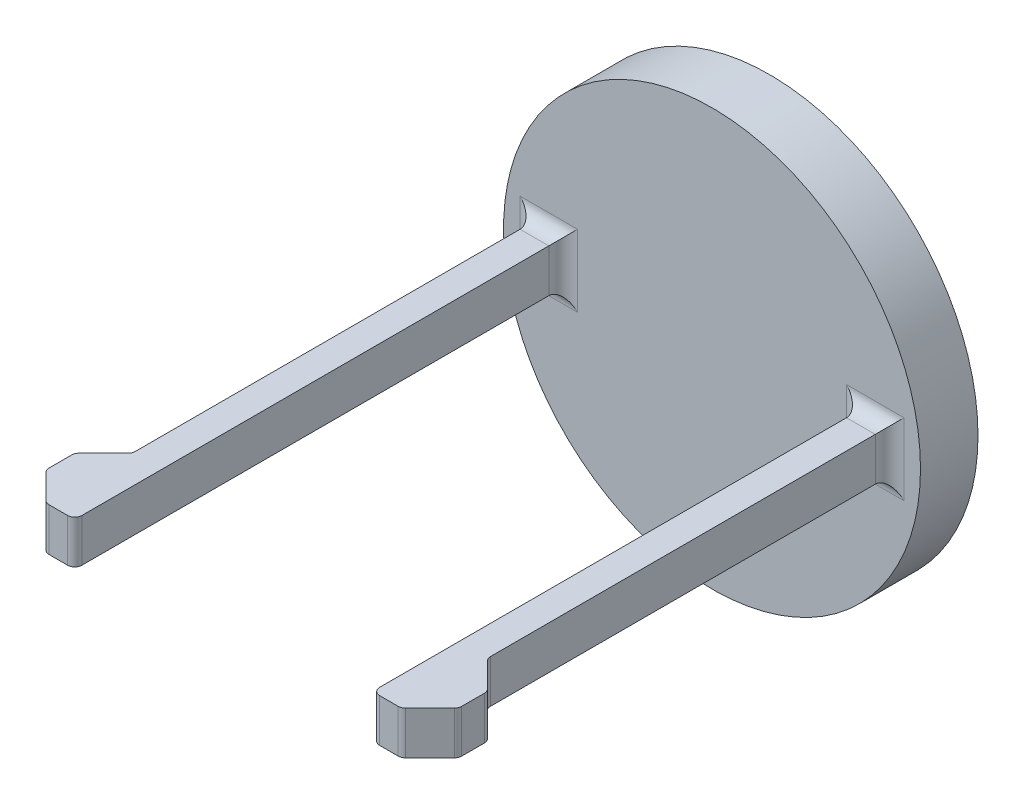
SolidWorks part; units mm, degrees
ref_plane "Front Plane" through (0, 0, 0) normal (1, 0, 0) x (0, 1, 0)
ref_plane "Top Plane" through (0, 0, 0) normal (0, 0, 1) x (0, 1, 0)
ref_plane "Right Plane" through (0, 0, 0) normal (0, 1, 0) x (-1, 0, 0)
sketch "Sketch1" plane through (0, 0, 0) normal (0, 0, 1) x (0, 1, 0)
  circle A0 centre (0, 0) radius 14.5
  dimension "D1" = 29
extrude "Boss-Extrude1" add sketch "Sketch1" along normal blind 4
sketch "Sketch2" plane through (0, 0, 4) normal (0, 0, 1) x (1, 0, 0)
  line L0 (0, 0) -> (-14.5, 0) construction
  line L1 (0, 0) -> (14.5, 0) construction
  line L2 (0, 14.5) -> (0, 0) construction
  line L3 (-12.3535, 1.5) -> (-10.3535, 1.5)
  line L4 (-12.3535, 1.5) -> (-12.3535, -1.5)
  line L5 (-12.3535, -1.5) -> (-10.3535, -1.5)
  line L6 (-10.3535, 1.5) -> (-10.3535, -1.5)
  line L7 (-12.3535, 1.5) -> (-10.3535, -1.5) construction
  line L8 (-12.3535, -1.5) -> (-10.3535, 1.5) construction
  line L9 (0, 0) -> (0, -14.5) construction
  line L10 (12.3535, -1.5) -> (10.3535, -1.5)
  line L11 (10.3535, 1.5) -> (10.3535, -1.5)
  line L12 (12.3535, 1.5) -> (10.3535, 1.5)
  line L13 (12.3535, 1.5) -> (12.3535, -1.5)
  circle A0 centre (0, 0) radius 14.5 construction
  point P6 (-11.3535, 0)
  dimension "D1" = 2
  dimension "D2" = 3
extrude "Boss-Extrude2" add sketch "Sketch2" along normal blind 33.9738
sketch "Sketch3" plane through (-12.3535, 0, 0) normal (-1, 0, 0) x (0, -1, 0)
  line L0 (-1.5, 37.9738) -> (1.5, 37.9738) construction
  line L1 (-1.5, 37.9738) -> (1.5, 37.9738)
  line L2 (-1.5, 37.9738) -> (-1.5, 31.9738)
  line L3 (-1.5, 31.9738) -> (1.5, 31.9738)
  line L4 (1.5, 37.9738) -> (1.5, 31.9738)
  line L5 (1.5, 37.9738) -> (1.5, 4) construction
  dimension "D1" = 6
extrude "Boss-Extrude3" add sketch "Sketch3" along normal blind 2
sketch "Sketch4" plane through (0, -1.5, 0) normal (0, -1, 0) x (1, 0, 0)
  line L0 (-12.3535, 31.9738) -> (-14.3535, 33.9738)
  line L1 (-14.3535, 31.9738) -> (-14.3535, 37.9738) construction
  line L2 (-12.3535, 37.9738) -> (-14.3535, 35.9738)
  line L3 (-14.3535, 37.9738) -> (-10.3535, 37.9738) construction
  line L4 (-14.3535, 31.9738) -> (-12.3535, 31.9738) construction
  line L5 (-14.3535, 33.9738) -> (-14.3535, 31.9738)
  line L6 (-14.3535, 31.9738) -> (-12.3535, 31.9738)
  line L7 (-14.3535, 35.9738) -> (-14.3535, 37.9738)
  line L8 (-14.3535, 37.9738) -> (-12.3535, 37.9738)
  dimension "D1" = 45
  dimension "D2" = 45
extrude "Cut-Extrude1" cut sketch "Sketch4" against normal up to next
sketch "Sketch5" plane through (12.3535, 0, 0) normal (1, 0, 0) x (0, 1, 0)
  line L0 (1.5, 37.9738) -> (1.5, 4) construction
  line L1 (-1.5, 37.9738) -> (1.5, 37.9738)
  line L2 (-1.5, 37.9738) -> (-1.5, 31.9738)
  line L3 (-1.5, 31.9738) -> (1.5, 31.9738)
  line L4 (1.5, 37.9738) -> (1.5, 31.9738)
  dimension "D1" = 6
extrude "Boss-Extrude4" add sketch "Sketch5" along normal blind 2
sketch "Sketch6" plane through (0, -1.5, 0) normal (0, -1, 0) x (1, 0, 0)
  line L0 (12.3535, 31.9738) -> (14.3535, 33.9738)
  line L1 (14.3535, 37.9738) -> (14.3535, 31.9738) construction
  line L2 (14.3535, 33.9738) -> (14.3535, 31.9738)
  line L3 (14.3535, 31.9738) -> (12.3535, 31.9738)
  line L4 (12.3535, 37.9738) -> (14.3535, 35.9738)
  line L5 (10.3535, 37.9738) -> (14.3535, 37.9738) construction
  line L6 (14.3535, 35.9738) -> (14.3535, 37.9738)
  line L7 (14.3535, 37.9738) -> (12.3535, 37.9738)
  dimension "D1" = 45
  dimension "D2" = 45
extrude "Cut-Extrude2" cut sketch "Sketch6" against normal up to next
fillet "Fillet1" radius 1 8 edges at (-11.3535, -1.5, 4) (-10.3535, 0, 4) (-11.3535, 1.5, 4) (11.3535, -1.5, 4) (10.3535, 0, 4) (11.3535, 1.5, 4) (-12.3535, 0, 4) (12.3535, 0, 4)
fillet "Fillet2" radius 0.5 10 edges at (-12.3535, 0, 31.9738) (-14.3535, 0, 33.9738) (-14.3535, 0, 35.9738) (-12.3535, 0, 37.9738) (-10.3535, 0, 37.9738) (10.3535, 0, 37.9738) (12.3535, 0, 37.9738) (14.3535, 0, 35.9738) (14.3535, 0, 33.9738) (12.3535, 0, 31.9738)
equation "\"length\"= ( ( \"base\" * ( \"height\" ^ 3 ) * \"delta\" * \"E\" ) / ( 6 * 0.67 * \"force\" ) ) ^ ( 1 / 3 )"
equation "\"height\"= 2"
equation "\"delta\"= 2"
equation "\"force\"= 1.5"
equation "\"E\"= 2750"
equation "\"diameter\"= 25mm + 2 * 2"
equation "\"t\"= 4mm"
equation "\"D1@Sketch1\"=\"diameter\""
equation "\"D1@Boss-Extrude1\"=\"t\""
equation "\"D1@Sketch2\"=\"height\""
equation "\"D2@Sketch2\"=\"base\""
equation "\"base\"= 3"
equation "\"D1@Boss-Extrude2\"=\"length\"+ \"flex_len\""
equation "\"D1@Sketch3\"=\"flex_len\""
equation "\"flex_len\"= 6"
equation "\"D1@Boss-Extrude3\"=\"delta\""
equation "\"D1@Sketch5\"=\"flex_len\""
equation "\"D1@Boss-Extrude4\"=\"delta\""
equation "\"cap_height\"= 50"
equation "\"clearance\"= 0.2"
